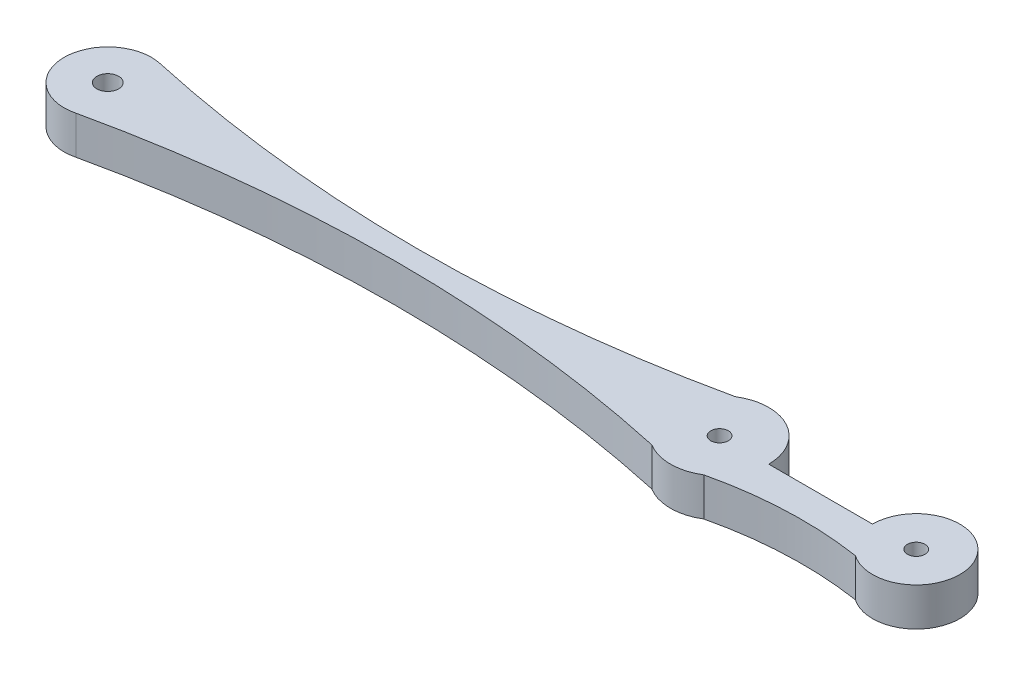
SolidWorks part; units mm, degrees
ref_plane "Ön Düzlem" through (0, 0, 0) normal (0, 0, 1) x (1, 0, 0)
ref_plane "Üst Düzlem" through (0, 0, 0) normal (0, 1, 0) x (1, 0, 0)
ref_plane "Sağ Düzlem" through (0, 0, 0) normal (1, 0, 0) x (0, 0, -1)
sketch "Sketch1" plane through (0, 0, 0) normal (0, 1, 0) x (1, 0, 0)
  line L0 (-112, 0) -> (57.4348, 0) construction
  circle A0 centre (0, 0) radius 9
  circle A1 centre (0, 0) radius 2.9808
  circle A2 centre (36, 0) radius 1.6
  circle A3 centre (36, 0) radius 8
  circle A4 centre (-112, 0) radius 2
  circle A5 centre (-112, 0) radius 8
  arc A6 (-110.0922, 7.7692) -> (-4.7568, 7.6402) centre (-57.1309, 247.4656) ccw
  arc A7 (4.7568, 7.6402) -> (31.4352, 6.5698) centre (20.8573, 75.9292) ccw
  arc A8 (4.7568, -7.6402) -> (31.4352, -6.5698) centre (20.8573, -75.9292) cw
  arc A9 (-110.0922, -7.7692) -> (-4.7568, -7.6402) centre (-57.1309, -247.4656) cw
  dimension "D1" = 16
  dimension "D2" = 4
  dimension "D3" = 18
  dimension "D4" = 5.9616
  dimension "D5" = 3.2
  dimension "D6" = 16
  dimension "D7" = 36
  dimension "D8" = 112
extrude "Boss-Extrude1" add sketch "Sketch1" along normal blind 7
sketch "Sketch3" plane through (0, 7, 0) normal (0, 1, 0) x (1, 0, 0)
  circle A0 centre (0, 0) radius 1.6
sketch "Sketch4" plane through (0, 7, 0) normal (0, 1, 0) x (1, 0, 0)
  circle A0 centre (0, 0) radius 1.6
extrude "Cut-Extrude1" cut sketch "Sketch4" against normal blind 10
